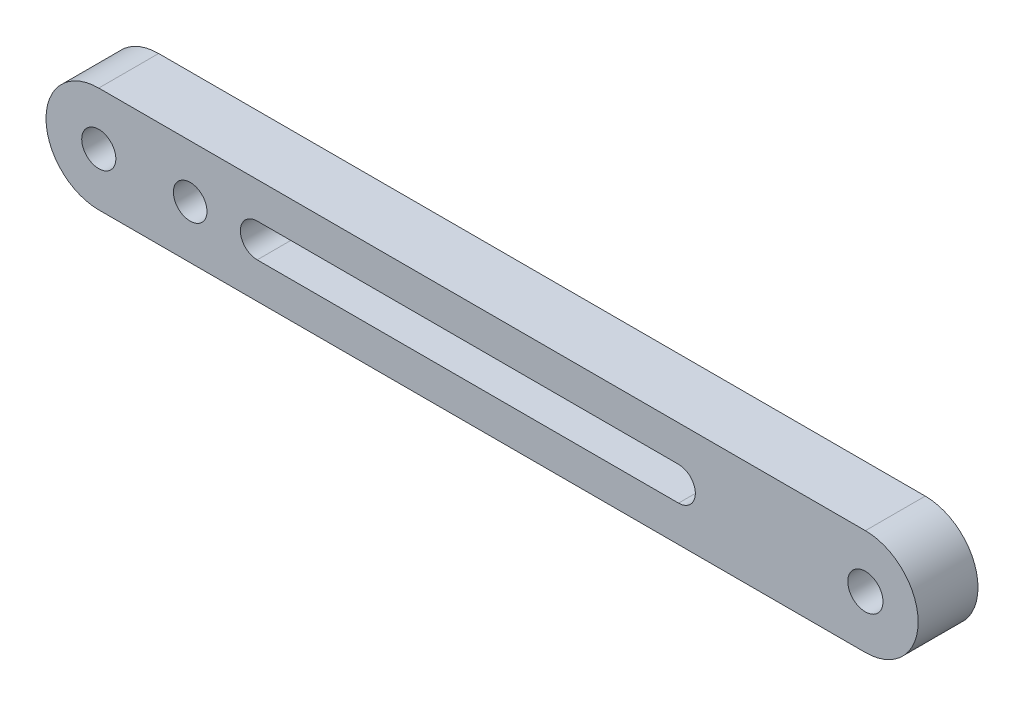
SolidWorks part; units mm, degrees
ref_plane "前视基准面" through (0, 0, 0) normal (0, 0, 1) x (1, 0, 0)
ref_plane "上视基准面" through (0, 0, 0) normal (0, 1, 0) x (1, 0, 0)
ref_plane "右视基准面" through (0, 0, 0) normal (1, 0, 0) x (0, 0, -1)
sketch "草图1" plane through (0, 0, 0) normal (0, 0, 1) x (1, 0, 0)
  line L0 (1.5398, 12.851) -> (15.553, 14.251)
  line L1 (-16.647, 18.901) -> (15.553, 18.901) construction
  line L2 (-16.647, 18.901) -> (-16.647, 12.851) construction
  line L3 (-16.647, 12.851) -> (15.553, 12.851) construction
  line L4 (15.553, 18.901) -> (15.553, 12.851) construction
  line L5 (-16.647, 18.901) -> (15.553, 12.851) construction
  line L6 (-16.647, 12.851) -> (15.553, 18.901) construction
  line L7 (14.1183, 17.876) -> (16.9877, 17.876) construction
  line L8 (14.1183, 17.876) -> (14.1183, 13.876) construction
  line L9 (14.1183, 13.876) -> (16.9877, 13.876) construction
  line L10 (16.9877, 17.876) -> (16.9877, 13.876) construction
  line L11 (14.1183, 17.876) -> (16.9877, 13.876) construction
  line L12 (14.1183, 13.876) -> (16.9877, 17.876) construction
  line L13 (15.553, 17.876) -> (1.5005, 18.901)
  line L14 (-0.547, 19.551) -> (-0.547, 12.201) construction
  line L15 (-0.547, 19.551) -> (-0.547, 20.901)
  line L16 (-0.547, 20.901) -> (19.5128, 20.901)
  line L17 (19.5128, 20.901) -> (41.453, 20.901)
  line L18 (-0.547, 12.201) -> (-0.547, 10.851)
  line L19 (-0.547, 10.851) -> (41.453, 10.851)
  line L20 (41.453, 20.901) -> (41.453, 10.851)
  line L21 (-0.547, 15.876) -> (3.9081, 15.876) construction
  circle A0 centre (-0.547, 15.876) radius 3.675 construction
  arc A1 (15.553, 14.251) -> (15.553, 17.876) centre (15.3719, 16.0635) ccw
  arc A2 (1.5398, 12.851) -> (-0.547, 12.201) centre (-0.547, 15.876) cw
  arc A3 (1.5005, 18.901) -> (-0.547, 19.551) centre (-0.547, 16.001) ccw
  point P6 (15.553, 15.876)
  dimension "D1" = 7.35
  dimension "D2" = 16.1
  dimension "D3" = 6.05
  dimension "D4" = 4
  dimension "D5" = 2
  dimension "D6" = 2
  dimension "D7" = 42
  dimension "D8" = 10.05
extrude "凸台-拉伸1" add sketch "草图1" along normal blind 2.2
sketch "草图2" plane through (0, 0, 0) normal (0, 0, -1) x (-1, 0, 0)
  line L0 (-19.5128, 10.851) -> (-49.453, 10.851)
  line L1 (-19.5128, 20.901) -> (0.547, 20.901)
  line L2 (-49.453, 10.851) -> (-49.453, 20.901)
  line L3 (-19.5128, 10.851) -> (0.547, 10.851)
  line L4 (0.547, 20.901) -> (0.547, 10.851)
  line L5 (-49.453, 20.901) -> (-19.5128, 20.901)
extrude "凸台-拉伸2" add sketch "草图2" along normal blind 3.25
sketch "草图3" plane through (0, 0, 2.2) normal (0, 0, 1) x (1, 0, 0)
  line L1 (-0.547, 20.901) -> (49.453, 20.901)
  line L3 (-0.547, 20.901) -> (-0.547, 10.851)
  line L4 (-0.547, 10.851) -> (49.453, 10.851)
  line L5 (49.453, 20.901) -> (49.453, 10.851)
extrude "凸台-拉伸3" add sketch "草图3" along normal blind 3.25
sketch "草图4" plane through (0, 0, 0) normal (0, 0, 1) x (1, 0, 0)
  line L0 (1.5005, 18.901) -> (1.5398, 12.851) construction
  line L1 (-0.547, 20.901) -> (-0.547, 10.851) construction
  line L2 (-0.547, 19.551) -> (-2.2354, 16.6161)
  line L3 (-2.2354, 16.6161) -> (-1.1109, 12.3105)
  line L4 (-1.1109, 12.3105) -> (-0.547, 12.201)
  arc A0 (1.5398, 12.851) -> (-0.547, 12.201) centre (-0.547, 15.876) cw
  arc A1 (-0.547, 19.551) -> (1.5398, 12.851) centre (-0.547, 15.876) ccw construction
  arc A2 (1.5005, 18.901) -> (-0.547, 19.551) centre (-0.547, 16.001) ccw
  arc A3 (1.5005, 18.901) -> (-0.547, 19.551) centre (-0.547, 16.001) ccw construction
  arc A4 (1.5005, 18.901) -> (1.5398, 12.851) centre (-1.5048, 15.8564) cw
extrude "切除-拉伸1" cut sketch "草图4" against normal mid plane 60
sketch "草图6" plane through (0, 0, -3.25) normal (0, 0, -1) x (-1, 0, 0)
  line L0 (-49.453, 15.876) -> (-51.7312, 15.876) construction
  line L2 (-49.453, 20.901) -> (-49.453, 10.851) construction
  circle A0 centre (-49.453, 15.876) radius 5.025
extrude "凸台-拉伸4" add sketch "草图6" against normal up to surface (8.7 mm away) up to face at (12.6389, 15.877, 5.45)
sketch "草图7" plane through (41.453, 0, 0) normal (1, 0, 0) x (0, 0, -1)
  line L0 (-1.1, 20.901) -> (-1.1, 19.7727) construction
  line L3 (-2.6, 22.1945) -> (0.4, 22.1945)
  line L4 (-2.6, 22.1945) -> (-2.6, 10.0543)
  line L5 (-2.6, 10.0543) -> (0.4, 10.0543)
  line L6 (0.4, 22.1945) -> (0.4, 10.0543)
  line L7 (-2.6, 22.1945) -> (0.4, 10.0543) construction
  line L8 (-2.6, 10.0543) -> (0.4, 22.1945) construction
  point P1 (-1.1, 16.1244)
  dimension "D1" = 3
sketch "草图8" plane through (0, 0, -3.25) normal (0, 0, -1) x (-1, 0, 0)
  line L0 (0.547, 19.551) -> (0.547, 20.901) construction
  circle A0 centre (-49.453, 15.876) radius 1.675
  circle A1 centre (-7.953, 15.8564) radius 0.84
  dimension "D1" = 3.35
  dimension "D2" = 1.68
  dimension "D3" = 8.5
extrude "切除-拉伸3" cut sketch "草图8" against normal blind 55
sketch "草图9" plane through (0, 0, -3.25) normal (0, 0, -1) x (-1, 0, 0)
  line L1 (-28.4121, 22.3056) -> (-56.8851, 22.3056)
  line L2 (-28.4121, 22.3056) -> (-28.4121, 7.7732)
  line L3 (-28.4121, 7.7732) -> (-56.8851, 7.7732)
  line L4 (-56.8851, 22.3056) -> (-56.8851, 7.7732)
extrude "切除-拉伸4" cut sketch "草图9" against normal blind 3
sketch "草图10" plane through (0, 0, 2.2) normal (0, 0, -1) x (-1, 0, 0)
  line L0 (-49.453, 20.901) -> (-38.4664, 20.901)
  line L1 (-49.453, 20.901) -> (-28.4121, 20.901) construction
  line L2 (-38.4664, 20.901) -> (-38.4664, 10.851)
  line L3 (-28.4121, 10.851) -> (-49.453, 10.851) construction
  line L4 (-38.4664, 10.851) -> (-49.453, 10.851)
  arc A0 (-49.453, 10.851) -> (-49.453, 20.901) centre (-51.7381, 15.876) ccw
extrude "凸台-拉伸5" add sketch "草图10" along normal up to surface (2.45 mm away) up to face at (51.128, 15.876, -0.25)
sketch "草图11" plane through (0, 0, -3.25) normal (0, 0, -1) x (-1, 0, 0)
  line L0 (-49.453, 20.901) -> (-28.4121, 20.901) construction
  line L1 (-38.9326, 20.901) -> (-26.3184, 20.901)
  line L2 (-38.9326, 20.901) -> (-38.9326, 10.851)
  line L3 (-38.9326, 10.851) -> (-26.3184, 10.851)
  line L4 (-26.3184, 20.901) -> (-26.3184, 10.851)
  line L5 (-28.4121, 10.851) -> (0.547, 10.851) construction
extrude "凸台-拉伸6" add sketch "草图11" against normal up to surface (3 mm away) up to face at (40.1888, 15.876, -0.25)
sketch "草图12" plane through (0, 0, -3.25) normal (0, 0, -1) x (-1, 0, 0)
  line L0 (-38.9326, 20.901) -> (-38.9326, 10.851) construction
  line L1 (-23.9326, 22.7776) -> (12.6959, 22.7776)
  line L2 (-23.9326, 22.7776) -> (-23.9326, 7.4291)
  line L3 (-23.9326, 7.4291) -> (12.6959, 7.4291)
  line L4 (12.6959, 22.7776) -> (12.6959, 7.4291)
  point P6 (-38.9326, 15.876)
  dimension "D1" = 15
extrude "切除-拉伸5" cut sketch "草图12" against normal blind 10 contours L4 L3 L2 L1
sketch "草图13" plane through (23.9326, 0, 0) normal (-1, 0, 0) x (0, 0, 1)
  line L1 (-1.575, 18.7994) -> (3.775, 18.7994)
  line L2 (-1.575, 18.7994) -> (-1.575, 13.4494)
  line L3 (-1.575, 13.4494) -> (3.775, 13.4494)
  line L4 (3.775, 18.7994) -> (3.775, 13.4494)
  line L5 (-1.575, 18.7994) -> (3.775, 13.4494) construction
  line L6 (-1.575, 13.4494) -> (3.775, 18.7994) construction
  point P0 (1.1, 16.1244)
  dimension "D1" = 5.35
  dimension "D2" = 5.35
extrude "切除-拉伸6" cut sketch "草图13" against normal blind 14
sketch "草图14" plane through (0, 20.901, 0) normal (0, 1, 0) x (1, 0, 0)
  circle A0 centre (30.5382, -1.1) radius 1.1
  dimension "D1" = 2.2
extrude "切除-拉伸7" cut sketch "草图14" against normal blind 14
sketch "草图15" plane through (0, 0, 5.45) normal (0, 0, 1) x (1, 0, 0)
  circle A0 centre (36.8799, 15.8828) radius 1.1
extrude "切除-拉伸8" cut sketch "草图15" against normal blind 10
sketch "草图16" plane through (0, 0, -0.25) normal (0, 0, -1) x (-1, 0, 0)
  line L1 (-49.453, 20.901) -> (23.547, 20.901)
  line L2 (-49.453, 20.901) -> (-49.453, 10.851)
  line L3 (-49.453, 10.851) -> (23.547, 10.851)
  circle A0 centre (23.547, 15.876) radius 5.025 construction
  arc A1 (23.547, 20.901) -> (23.547, 10.851) centre (23.547, 15.876) cw
  circle A2 centre (23.547, 15.876) radius 1.625
  dimension "D2" = 3.25
  dimension "D1" = 73
extrude "凸台-拉伸7" add sketch "草图16" against normal up to surface (5.7 mm away) up to face at (37.9799, 15.8828, 5.45)
sketch "草图17" plane through (0, 0, -3.25) normal (0, 0, -1) x (-1, 0, 0)
  line L1 (-43.1398, 23.5488) -> (-23.2167, 23.5488)
  line L2 (-43.1398, 23.5488) -> (-43.1398, 8.4657)
  line L3 (-43.1398, 8.4657) -> (-23.2167, 8.4657)
  line L4 (-23.2167, 23.5488) -> (-23.2167, 8.4657)
extrude "切除-拉伸9" cut sketch "草图17" against normal up to surface (3 mm away) up to face at (-25.172, 15.876, -0.25)
sketch "草图18" plane through (0, 0, -0.25) normal (0, 0, -1) x (-1, 0, 0)
  line L0 (-49.453, 17.551) -> (-49.453, 14.201) construction
  line L1 (-31.6616, 15.876) -> (8.461, 15.876) construction
  line L2 (-31.6616, 17.476) -> (8.461, 17.476)
  line L3 (-31.6616, 14.276) -> (8.461, 14.276)
  circle A0 centre (-49.453, 15.876) radius 1.675
  arc A1 (-31.6616, 17.476) -> (-31.6616, 14.276) centre (-31.6616, 15.876) ccw
  arc A2 (8.461, 14.276) -> (8.461, 17.476) centre (8.461, 15.876) ccw
  circle A3 centre (14.8432, 15.876) radius 1.6
  point P6 (-11.6003, 15.876)
  dimension "D1" = 3.2
  dimension "D2" = 1.6
extrude "切除-拉伸10" cut sketch "草图18" against normal blind 6
